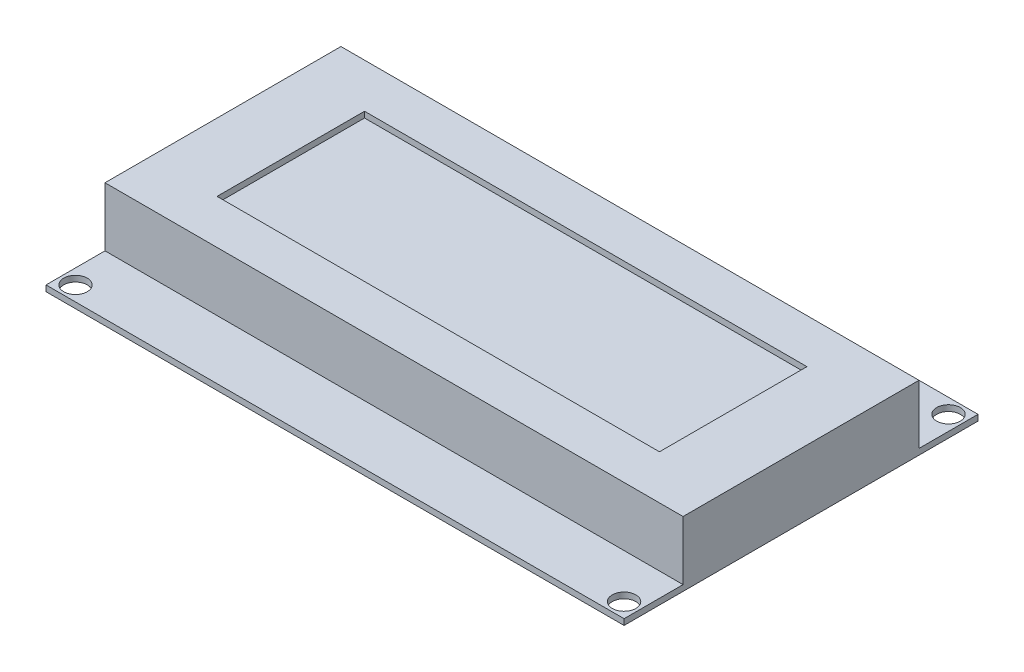
SolidWorks part; units mm, degrees
ref_plane "Plan de face" through (0, 0, 0) normal (0, 0, 1) x (1, 0, 0)
ref_plane "Plan de dessus" through (0, 0, 0) normal (0, 1, 0) x (1, 0, 0)
ref_plane "Plan de droite" through (0, 0, 0) normal (1, 0, 0) x (0, 0, -1)
sketch "Esquisse1" plane through (0, 0, 0) normal (0, 1, 0) x (1, 0, 0)
  line L0 (-46.5, 30) -> (-46.5, 24.1684) construction
  line L1 (-49, 30) -> (49, 30)
  line L2 (-49, 30) -> (-49, -30)
  line L3 (-49, -30) -> (49, -30)
  line L4 (49, 30) -> (49, -30)
  line L5 (-49, 30) -> (49, -30) construction
  line L6 (-49, -30) -> (49, 30) construction
  line L7 (-49, 27.5) -> (-43.6542, 27.5) construction
  line L8 (0, 0) -> (0, 50000) construction
  line L9 (0, 0) -> (50000, 0) construction
  circle A0 centre (-46.5, 27.5) radius 2
  circle A1 centre (46.5, 27.5) radius 2
  circle A2 centre (46.5, -27.5) radius 2
  circle A3 centre (-46.5, -27.5) radius 2
  circle A4 centre (-39, 27.5) radius 0.6379
  circle A5 centre (-37, 27.5) radius 0.6379
  circle A6 centre (-35, 27.5) radius 0.6379
  circle A7 centre (-33, 27.5) radius 0.6379
  circle A8 centre (-31, 27.5) radius 0.6379
  circle A9 centre (-29, 27.5) radius 0.6379
  circle A10 centre (-27, 27.5) radius 0.6379
  circle A11 centre (-25, 27.5) radius 0.6379
  circle A12 centre (-23, 27.5) radius 0.6379
  circle A13 centre (-21, 27.5) radius 0.6379
  circle A14 centre (-19, 27.5) radius 0.6379
  circle A15 centre (-17, 27.5) radius 0.6379
  circle A16 centre (-15, 27.5) radius 0.6379
  circle A17 centre (-13, 27.5) radius 0.6379
  circle A18 centre (-11, 27.5) radius 0.6379
  circle A19 centre (-9, 27.5) radius 0.6379
  point P0 (0, 0)
  point P10 (-46.5, 27.5)
  point P25 (0, 0)
  dimension "D5" = 4
  dimension "D7" = 7.5
  dimension "D1" = 98
  dimension "D2" = 60
  dimension "D3" = 2.5
  dimension "D4" = 2.5
  dimension "D6" = 16
extrude "Boss.-Extru.1" add sketch "Esquisse1" along normal mid plane 1
sketch "Esquisse3" plane through (0, 0.5, 0) normal (0, 1, 0) x (1, 0, 0)
  line L0 (49, -30) -> (49, 30) construction
  line L1 (-49, 20) -> (49, 20)
  line L2 (-49, 20) -> (-49, -20)
  line L3 (-49, -20) -> (49, -20)
  line L4 (49, 20) -> (49, -20)
  line L5 (-49, 20) -> (49, -20) construction
  line L6 (-49, -20) -> (49, 20) construction
  point P0 (0, 0)
  dimension "D1" = 40
extrude "Boss.-Extru.2" add sketch "Esquisse3" along normal blind 10
sketch "Esquisse4" plane through (0, 10.5, 0) normal (0, 1, 0) x (1, 0, 0)
  line L1 (-37.5, 12.5) -> (37.5, 12.5)
  line L2 (-37.5, 12.5) -> (-37.5, -12.5)
  line L3 (-37.5, -12.5) -> (37.5, -12.5)
  line L4 (37.5, 12.5) -> (37.5, -12.5)
  line L5 (-37.5, 12.5) -> (37.5, -12.5) construction
  line L6 (-37.5, -12.5) -> (37.5, 12.5) construction
  point P0 (0, 0)
  dimension "D1" = 75
  dimension "D2" = 25
extrude "Enlèv. mat.-Extru.1" cut sketch "Esquisse4" against normal blind 1
sketch "Esquisse5" plane through (0, -0.5, 0) normal (0, -1, 0) x (1, 0, 0)
  line L0 (-40, -27.25) -> (-40, -22)
  line L1 (2, -27.25) -> (-40, -27.25)
  line L2 (2, -27.25) -> (2, -8.25)
  line L3 (2, -8.25) -> (-40, -8.25)
  line L5 (-40, -22) -> (-47, -22)
  line L6 (-47, -22) -> (-47, -13.5)
  line L7 (-47, -13.5) -> (-40, -13.5)
  line L8 (-40, -13.5) -> (-40, -8.25)
  line L10 (-49, -30) -> (-49, 30) construction
  line L11 (49, -30) -> (-49, -30) construction
  dimension "D1" = 8
  dimension "D2" = 42
  dimension "D3" = 19
  dimension "D4" = 8.5
  dimension "D5" = 7
  dimension "D6" = 9
extrude "Boss.-Extru.4" add sketch "Esquisse5" along normal blind 10
